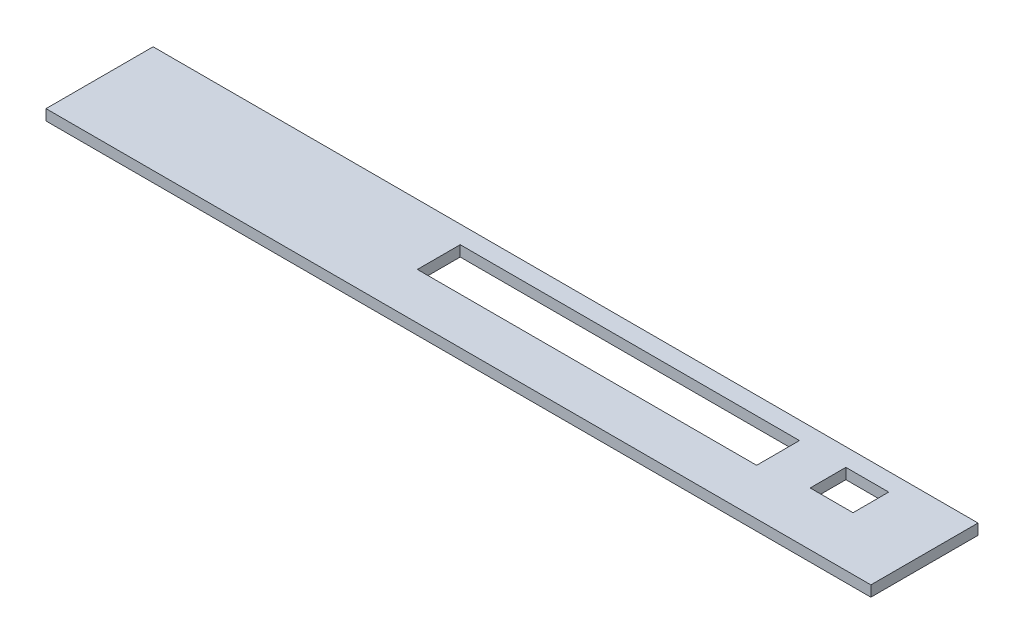
SolidWorks part; units mm, degrees
ref_plane "前基準面" through (0, 0, 0) normal (0, 0, 1) x (1, 0, 0)
ref_plane "上基準面" through (0, 0, 0) normal (0, 1, 0) x (1, 0, 0)
ref_plane "右基準面" through (0, 0, 0) normal (1, 0, 0) x (0, 0, -1)
sketch "草圖1" plane through (0, 0, 0) normal (0, 1, 0) x (1, 0, 0)
  line L0 (0, 0) -> (231, 0)
  line L1 (231, 0) -> (231, 30)
  line L2 (231, 30) -> (0, 30)
  line L3 (0, 30) -> (0, 0)
  dimension "D1" = 231
  dimension "D2" = 30
extrude "填料-伸長1" add sketch "草圖1" along normal blind 3
sketch "草圖2" plane through (0, 3, 0) normal (0, 1, 0) x (1, 0, 0)
  line L1 (91, 25) -> (186, 25)
  line L2 (91, 25) -> (91, 13)
  line L3 (91, 13) -> (186, 13)
  line L4 (186, 25) -> (186, 13)
  line L5 (231, 30) -> (0, 30) construction
  line L6 (231, 0) -> (231, 30) construction
  line L8 (199, 25) -> (211, 25)
  line L9 (199, 25) -> (199, 15)
  line L10 (199, 15) -> (211, 15)
  line L11 (211, 25) -> (211, 15)
  dimension "D1" = 12
  dimension "D2" = 95
  dimension "D3" = 5
  dimension "D4" = 45
  dimension "D5" = 12
  dimension "D6" = 10
  dimension "D7" = 5
  dimension "D8" = 20
extrude "除料-伸長1" cut sketch "草圖2" against normal through all
equation "\"`8\"=15"
